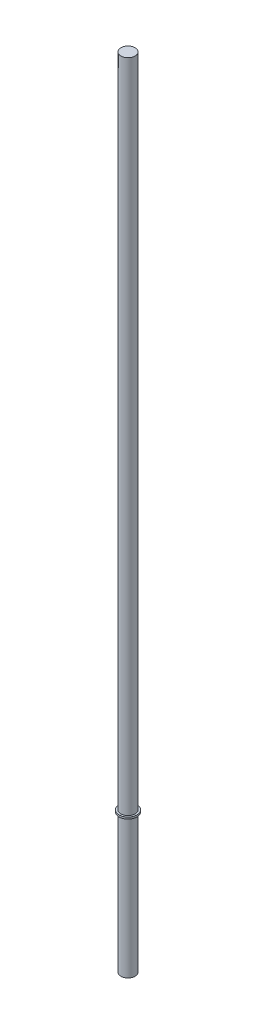
SolidWorks part; units mm, degrees
ref_plane "Plano frontal" through (0, 0, 0) normal (0, 0, 1) x (1, 0, 0)
ref_plane "Plano superior" through (0, 0, 0) normal (0, 1, 0) x (1, 0, 0)
ref_plane "Plano direito" through (0, 0, 0) normal (1, 0, 0) x (0, 0, -1)
sketch "Esboço1" plane through (0, 0, 0) normal (0, 1, 0) x (1, 0, 0)
  circle A0 centre (0, 0) radius 4
extrude "Ressalto-extrusão2" add sketch "Esboço1" along normal blind 445.1
sketch "Esboço2" plane through (0, 0, 0) normal (0, 0, 1) x (1, 0, 0)
  line L0 (0, 78.55) -> (5, 78.55)
  line L1 (5, 78.55) -> (5, 77.55)
  line L2 (5, 77.55) -> (0, 77.55)
  line L3 (0, 77.55) -> (0, 78.55)
  point P4 (0, 0)
  point P5 (0, 0)
  point P6 (0, 0)
  point P7 (0, 0)
  point P8 (0, 0)
  point P9 (0, 0)
  point P10 (0, 0)
  point P11 (0, 0)
  point P12 (0, 0)
  point P13 (0, 0)
revolve "Revolução1" add sketch "Esboço2" angle 360 about L3
